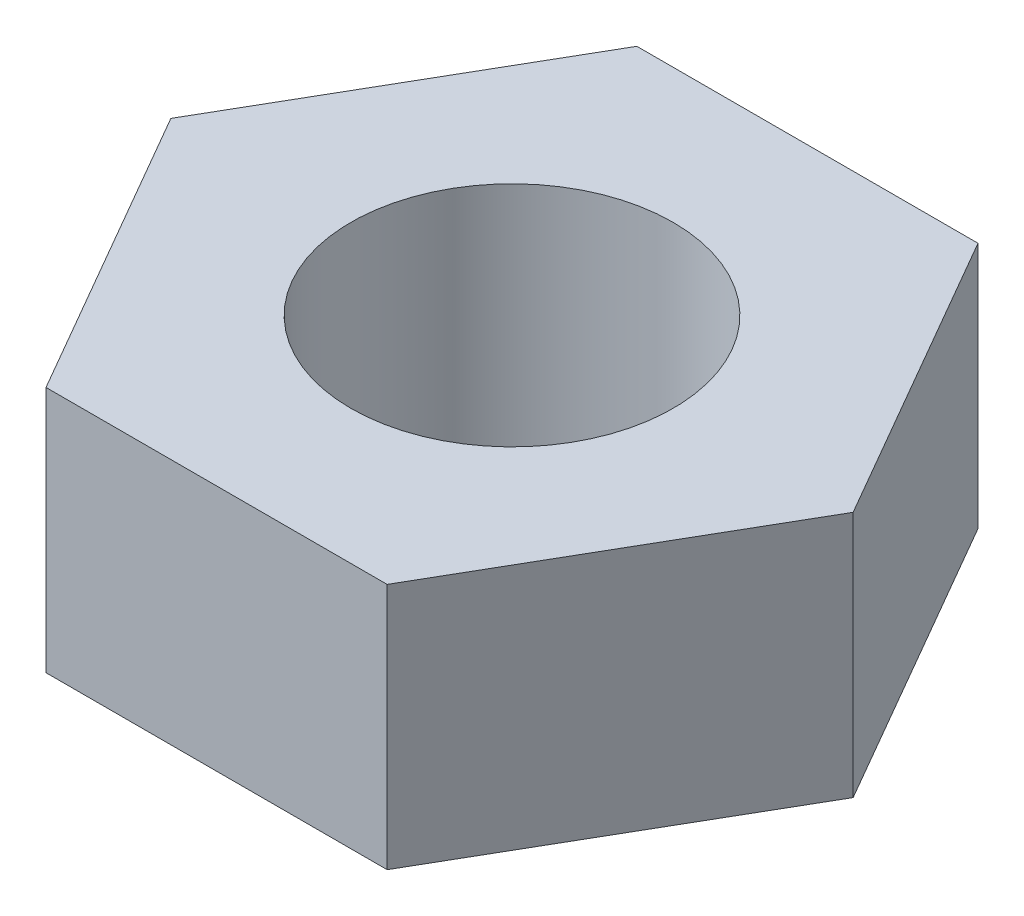
SolidWorks part; units mm, degrees
ref_plane "前视基准面" through (0, 0, 0) normal (0, 0, 1) x (1, 0, 0)
ref_plane "上视基准面" through (0, 0, 0) normal (0, 1, 0) x (1, 0, 0)
ref_plane "右视基准面" through (0, 0, 0) normal (1, 0, 0) x (0, 0, -1)
other "Configuration Table"
sketch "草图1" plane through (0, 0, 0) normal (0, 1, 0) x (1, 0, 0)
  line L1 (3.1754, 0) -> (1.5877, 2.75)
  line L2 (1.5877, 2.75) -> (-1.5877, 2.75)
  line L3 (-1.5877, 2.75) -> (-3.1754, 0)
  line L4 (-3.1754, 0) -> (-1.5877, -2.75)
  line L5 (-1.5877, -2.75) -> (1.5877, -2.75)
  line L6 (1.5877, -2.75) -> (3.1754, 0)
  circle A0 centre (0, 0) radius 2.75 construction
  circle A1 centre (0, 0) radius 1.5
  dimension "D1" = 5.5
  dimension "D2" = 3
extrude "凸台-拉伸1" add sketch "草图1" along normal blind 2.3
